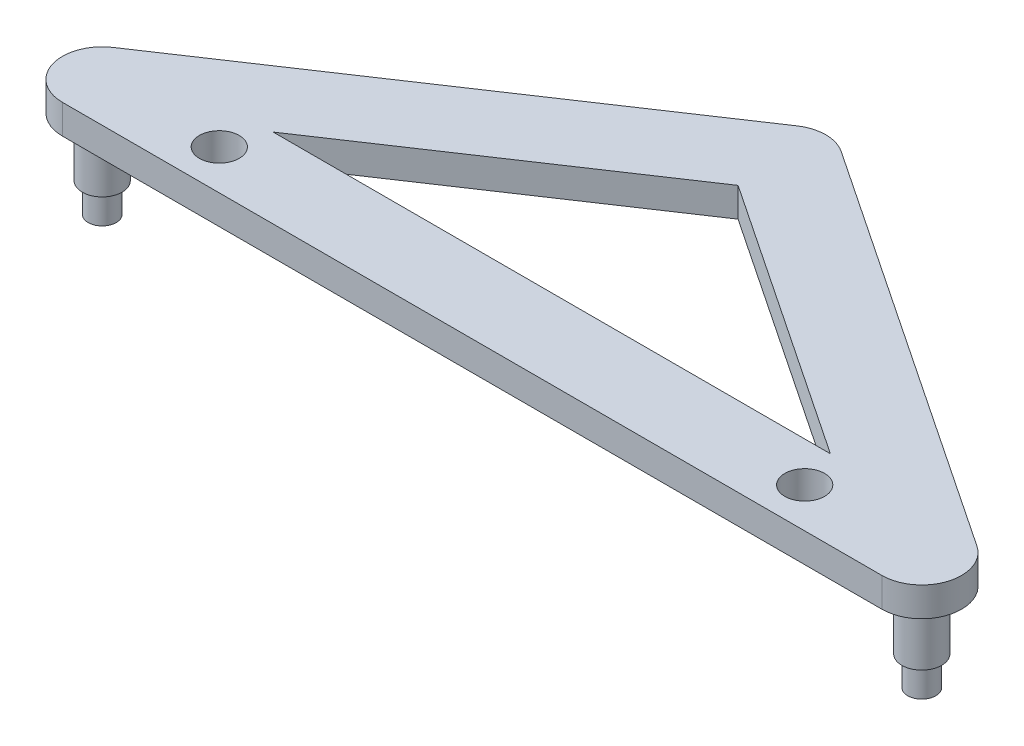
SolidWorks part; units mm, degrees
ref_plane "Front Plane" through (0, 0, 0) normal (0, 0, 1) x (1, 0, 0)
ref_plane "Top Plane" through (0, 0, 0) normal (0, 1, 0) x (1, 0, 0)
ref_plane "Right Plane" through (0, 0, 0) normal (1, 0, 0) x (0, 0, -1)
sketch "Sketch1" plane through (0, 0, 0) normal (0, 1, 0) x (1, 0, 0)
  circle A0 centre (0, 0) radius 1.7
  circle A1 centre (70, 0) radius 1.7
  dimension "D1" = 3.4
  dimension "D2" = 70
extrude "Boss-Extrude1" add sketch "Sketch1" along normal blind 5
sketch "Sketch2" plane through (0, 5, 0) normal (0, 1, 0) x (1, 0, 0)
  line L0 (0, 0) -> (70, 0) construction
  line L1 (0, 3.4) -> (70, 3.4)
  line L2 (0, -3.4) -> (70, -3.4)
  line L3 (35, 3.4) -> (35, -3.4) construction
  line L4 (35, 3.4) -> (35, 23.4)
  line L5 (0, 0) -> (35, 23.4) construction
  line L6 (-1.8897, 2.8265) -> (33.1103, 26.2265)
  line L7 (11.2028, 3.4) -> (35, 19.3101)
  line L8 (35, 23.4) -> (35, 26.8)
  line L9 (58.7972, 3.4) -> (35, 19.3101)
  line L10 (71.8897, 2.8265) -> (36.8897, 26.2265)
  arc A0 (0, 3.4) -> (0, -3.4) centre (0, 0) ccw
  arc A1 (70, -3.4) -> (70, 3.4) centre (70, 0) ccw
  circle A2 centre (10, 0) radius 1.7
  circle A3 centre (60, 0) radius 1.7
  arc A4 (-1.8897, 2.8265) -> (0, -3.4) centre (0, 0) ccw
  arc A5 (36.8897, 26.2265) -> (33.1103, 26.2265) centre (35, 23.4) ccw
  point P4 (35, 0)
  point P17 (17.5, 11.7)
  circle M7 centre (0, 0) radius 1.7
  dimension "D1" = 3.4
  dimension "D2" = 3.4
  dimension "D5" = 3.4
  dimension "D3" = 10
  dimension "D4" = 20
sketch "Sketch3" plane through (0, 0, 0) normal (0, -1, 0) x (1, 0, 0)
  circle A0 centre (0, 0) radius 1.2
  circle A1 centre (70, 0) radius 1.2
  dimension "D1" = 2.4
extrude "Boss-Extrude5" add sketch "Sketch2" along normal blind 2.5 contours L8 A5 L6 A0 L1 L7 L4 | M7 | L2 A1 L1 A0 A2 A3 M7 | L10 A5 L8 L4 L9 L1 A1
extrude "Boss-Extrude6" add sketch "Sketch3" along normal blind 2.5
sketch "Sketch4" plane through (0, 5, 0) normal (0, -1, 0) x (1, 0, 0)
  circle A0 centre (35, -23.4) radius 1.7
  dimension "D1" = 3.4
extrude "Boss-Extrude7" add sketch "Sketch4" along normal blind 5
